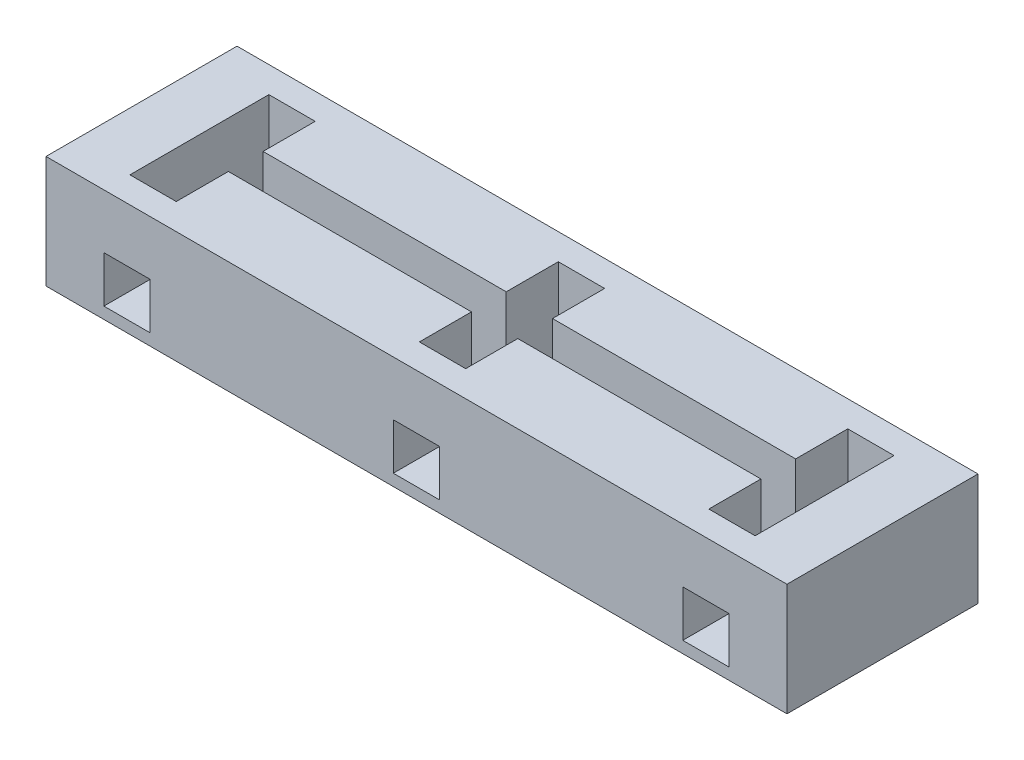
SolidWorks part; units mm, degrees
ref_plane "Front Plane" through (0, 0, 0) normal (0, 0, 1) x (1, 0, 0)
ref_plane "Top Plane" through (0, 0, 0) normal (0, 1, 0) x (1, 0, 0)
ref_plane "Right Plane" through (0, 0, 0) normal (1, 0, 0) x (0, 0, -1)
sketch "Sketch1" plane through (0, 0, 0) normal (0, 1, 0) x (1, 0, 0)
  line L0 (0, -397.7371) -> (0, 19489.1188) construction
  line L1 (-397.7371, 0) -> (19489.1188, 0) construction
  line L4 (-135, 30) -> (-115, 30)
  line L6 (-125, -979.4553) -> (-125, 49020.5447) construction
  line L7 (10, 30) -> (10, 7.5)
  line L8 (-160, -41.25) -> (-160, 41.25)
  line L9 (-160, -41.25) -> (160, -41.25)
  line L10 (-160, 41.25) -> (160, 41.25)
  line L11 (160, -41.25) -> (160, 41.25)
  line L12 (115, 7.5) -> (10, 7.5)
  line L13 (115, 30) -> (115, 7.5)
  line L18 (-135, 30) -> (-135, -30)
  line L20 (-115, 30) -> (-115, 7.5)
  line L21 (-115, 7.5) -> (-10, 7.5)
  line L22 (-10, 30) -> (-10, 7.5)
  line L38 (-10, 30) -> (10, 30)
  line L39 (135, 30) -> (135, -30)
  line L40 (135, 30) -> (115, 30)
  line L42 (135, -30) -> (115, -30)
  line L43 (115, -30) -> (115, -7.5)
  line L44 (115, -7.5) -> (10, -7.5)
  line L45 (10, -30) -> (10, -7.5)
  line L46 (-10, -30) -> (10, -30)
  line L47 (-10, -30) -> (-10, -7.5)
  line L48 (-115, -7.5) -> (-10, -7.5)
  line L49 (-115, -30) -> (-115, -7.5)
  line L50 (-135, -30) -> (-115, -30)
  point P5 (0, 0)
  point P7 (0, 0)
  point P21 (0, 30)
  point P27 (135, 0)
  point P36 (-135, 0)
  dimension "D1" = 320
  dimension "D2" = 125
  dimension "D3" = 82.5
  dimension "D4" = 20
  dimension "D5" = 10
  dimension "D6" = 30
  dimension "D7" = 7.5
extrude "Boss-Extrude1" add sketch "Sketch1" against normal blind 43.48
sketch "Sketch3" plane through (0, 0, 41.25) normal (0, 0, 1) x (1, 0, 0)
  line L0 (0, -1000) -> (0, 49000) construction
  line L2 (-10, -43.48) -> (10, -43.48)
  line L3 (-10, -43.48) -> (-10, -23.48)
  line L4 (-10, -23.48) -> (10, -23.48)
  line L5 (10, -43.48) -> (10, -23.48)
  line L6 (-10, -43.48) -> (10, -23.48) construction
  line L7 (-10, -23.48) -> (10, -43.48) construction
  line L8 (-125, -1023.1615) -> (-125, 48976.8385) construction
  line L9 (135, -23.48) -> (115, -23.48)
  line L10 (-135, -43.48) -> (-115, -43.48)
  line L11 (-135, -43.48) -> (-135, -23.48)
  line L12 (-135, -23.48) -> (-115, -23.48)
  line L13 (-115, -43.48) -> (-115, -23.48)
  line L14 (-135, -43.48) -> (-115, -23.48) construction
  line L15 (-135, -23.48) -> (-115, -43.48) construction
  line L16 (115, -43.48) -> (115, -23.48)
  line L17 (135, -43.48) -> (115, -43.48)
  line L18 (135, -43.48) -> (135, -23.48)
  line L19 (-160, -43.48) -> (160, -43.48) construction
  point P1 (0, -33.48)
  point P11 (-125, -33.48)
  dimension "D1" = 20
  dimension "D3" = 125
  dimension "D4" = 20
extrude "Cut-Extrude1" cut sketch "Sketch3" against normal blind 15
sketch "Sketch5" plane through (0, -43.48, 0) normal (0, -1, 0) x (1, 0, 0)
  line L0 (-160, 41.25) -> (-135, 41.25) construction
  line L1 (-160, 41.25) -> (160, 41.25)
  line L2 (-160, 41.25) -> (-160, -41.25)
  line L3 (-160, -41.25) -> (160, -41.25)
  line L4 (160, 41.25) -> (160, -41.25)
  line L5 (-160, -41.25) -> (-160, 41.25) construction
extrude "Boss-Extrude3" add sketch "Sketch5" along normal blind 5
